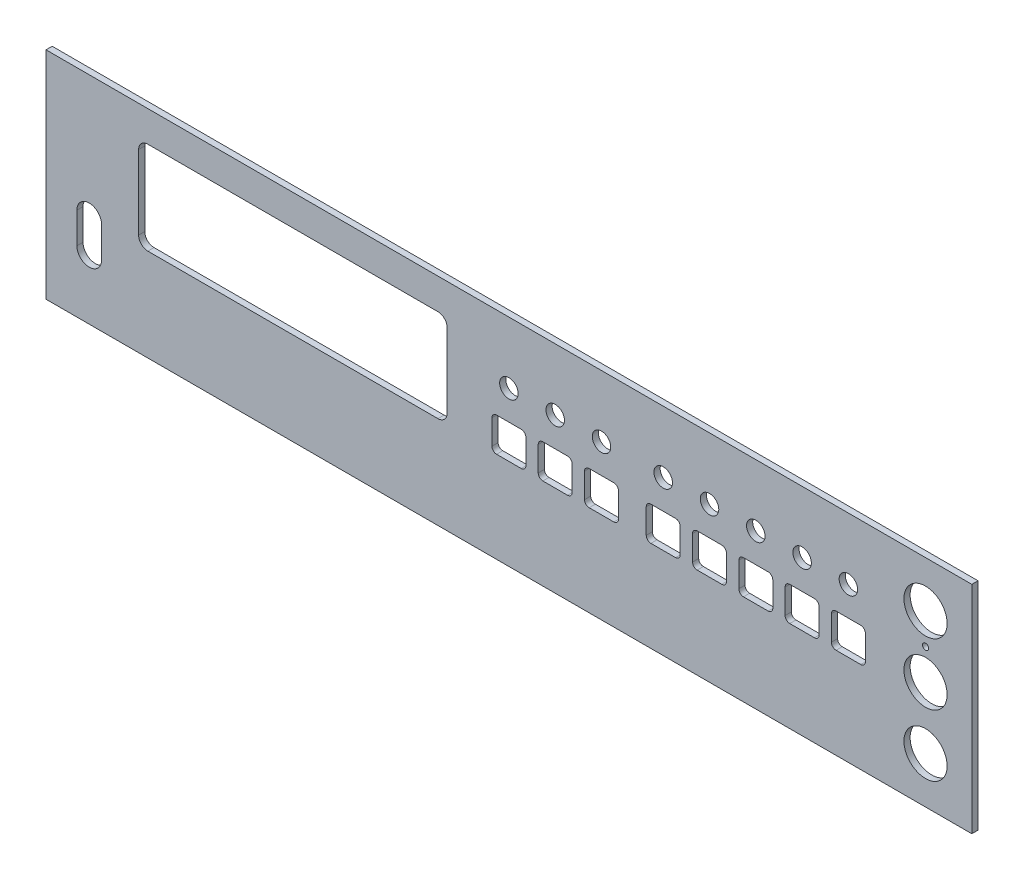
SolidWorks part; units mm, degrees
ref_plane "Спереди" through (0, 0, 0) normal (0, 0, 1) x (1, 0, 0)
ref_plane "Сверху" through (0, 0, 0) normal (0, 1, 0) x (1, 0, 0)
ref_plane "Справа" through (0, 0, 0) normal (1, 0, 0) x (0, 0, -1)
sketch "Эскиз1" plane through (0, 0, 0) normal (0, 0, 1) x (1, 0, 0)
  line L0 (-150, 35) -> (-150, -35) construction
  line L1 (-120, 25) -> (-120, -5) construction
  line L2 (-120, 25) -> (-20, 25) construction
  line L3 (-120, -5) -> (-20, -5) construction
  line L4 (-150, -35) -> (150, -35) construction
  line L5 (-150, 35) -> (150, 35) construction
  line L6 (150, 35) -> (150, -35) construction
  line L7 (70.5, 5.5) -> (70.5, -5.5) construction
  line L8 (59.5, 5.5) -> (70.5, 5.5) construction
  line L9 (59.5, 5.5) -> (59.5, -5.5) construction
  line L10 (59.5, -5.5) -> (70.5, -5.5) construction
  line L11 (74.5, -5.5) -> (85.5, -5.5) construction
  line L12 (74.5, 5.5) -> (74.5, -5.5) construction
  line L13 (74.5, 5.5) -> (85.5, 5.5) construction
  line L14 (85.5, 5.5) -> (85.5, -5.5) construction
  line L15 (89.5, 5.5) -> (89.5, -5.5) construction
  line L16 (89.5, 5.5) -> (100.5, 5.5) construction
  line L17 (100.5, 5.5) -> (100.5, -5.5) construction
  line L18 (104.5, 5.5) -> (104.5, -5.5) construction
  line L19 (89.5, -5.5) -> (100.5, -5.5) construction
  line L20 (104.5, -5.5) -> (115.5, -5.5) construction
  line L21 (115.5, 5.5) -> (115.5, -5.5) construction
  line L22 (104.5, 5.5) -> (115.5, 5.5) construction
  line L23 (44.5, 5.5) -> (55.5, 5.5) construction
  line L24 (44.5, 5.5) -> (44.5, -5.5) construction
  line L25 (44.5, -5.5) -> (55.5, -5.5) construction
  line L26 (55.5, 5.5) -> (55.5, -5.5) construction
  line L27 (9.5, -5.5) -> (9.5, 5.5) construction
  line L28 (9.5, 5.5) -> (20.5, 5.5) construction
  line L29 (20.5, -5.5) -> (20.5, 5.5) construction
  line L30 (9.5, -5.5) -> (20.5, -5.5) construction
  line L31 (24.5, 5.5) -> (35.5, 5.5) construction
  line L32 (35.5, -5.5) -> (35.5, 5.5) construction
  line L33 (24.5, -5.5) -> (35.5, -5.5) construction
  line L34 (24.5, -5.5) -> (24.5, 5.5) construction
  line L35 (-20, 25) -> (-20, -5) construction
  line L36 (-5.5, -5.5) -> (-5.5, 5.5) construction
  line L37 (-5.5, 5.5) -> (5.5, 5.5) construction
  line L38 (5.5, -5.5) -> (5.5, 5.5) construction
  line L39 (-5.5, -5.5) -> (5.5, -5.5) construction
  line L40 (-150, 35) -> (-150, -35)
  line L41 (-120, 25) -> (-120, -5)
  line L42 (-120, 25) -> (-20, 25)
  line L43 (-120, -5) -> (-20, -5)
  line L44 (-150, -35) -> (150, -35)
  line L45 (-150, 35) -> (150, 35)
  line L46 (150, 35) -> (150, -35)
  line L47 (70.5, 5.5) -> (70.5, -5.5)
  line L48 (59.5, 5.5) -> (70.5, 5.5)
  line L49 (59.5, 5.5) -> (59.5, -5.5)
  line L50 (59.5, -5.5) -> (70.5, -5.5)
  line L51 (74.5, -5.5) -> (85.5, -5.5)
  line L52 (74.5, 5.5) -> (74.5, -5.5)
  line L53 (74.5, 5.5) -> (85.5, 5.5)
  line L54 (85.5, 5.5) -> (85.5, -5.5)
  line L55 (89.5, 5.5) -> (89.5, -5.5)
  line L56 (89.5, 5.5) -> (100.5, 5.5)
  line L57 (100.5, 5.5) -> (100.5, -5.5)
  line L58 (104.5, 5.5) -> (104.5, -5.5)
  line L59 (89.5, -5.5) -> (100.5, -5.5)
  line L60 (104.5, -5.5) -> (115.5, -5.5)
  line L61 (115.5, 5.5) -> (115.5, -5.5)
  line L62 (104.5, 5.5) -> (115.5, 5.5)
  line L63 (44.5, 5.5) -> (55.5, 5.5)
  line L64 (44.5, 5.5) -> (44.5, -5.5)
  line L65 (44.5, -5.5) -> (55.5, -5.5)
  line L66 (55.5, 5.5) -> (55.5, -5.5)
  line L67 (9.5, -5.5) -> (9.5, 5.5)
  line L68 (9.5, 5.5) -> (20.5, 5.5)
  line L69 (20.5, -5.5) -> (20.5, 5.5)
  line L70 (9.5, -5.5) -> (20.5, -5.5)
  line L71 (24.5, 5.5) -> (35.5, 5.5)
  line L72 (35.5, -5.5) -> (35.5, 5.5)
  line L73 (24.5, -5.5) -> (35.5, -5.5)
  line L74 (24.5, -5.5) -> (24.5, 5.5)
  line L75 (-20, 25) -> (-20, -5)
  line L76 (-5.5, -5.5) -> (-5.5, 5.5)
  line L77 (-5.5, 5.5) -> (5.5, 5.5)
  line L78 (5.5, -5.5) -> (5.5, 5.5)
  line L79 (-5.5, -5.5) -> (5.5, -5.5)
  line L80 (-140, -5) -> (-140, -15) construction
  line L81 (-132, -5) -> (-132, -15) construction
  line L82 (-140, -5) -> (-140, -15)
  line L83 (-132, -5) -> (-132, -15)
  arc A0 (-132, -5) -> (-140, -5) centre (-136, -5) ccw construction
  circle A1 centre (135, 20) radius 7 construction
  circle A2 centre (135, 0) radius 7 construction
  circle A3 centre (135, -20) radius 7 construction
  circle A4 centre (110, 15) radius 3 construction
  circle A5 centre (95, 15) radius 3 construction
  circle A6 centre (80, 15) radius 3 construction
  circle A7 centre (65, 15) radius 3 construction
  circle A8 centre (50, 15) radius 3 construction
  circle A9 centre (30, 15) radius 3 construction
  circle A10 centre (15, 15) radius 3 construction
  circle A11 centre (0, 15) radius 3 construction
  arc A12 (-132, -5) -> (-140, -5) centre (-136, -5) ccw
  circle A13 centre (135, 20) radius 7
  circle A14 centre (135, 0) radius 7
  circle A15 centre (135, -20) radius 7
  circle A16 centre (110, 15) radius 3
  circle A17 centre (95, 15) radius 3
  circle A18 centre (80, 15) radius 3
  circle A19 centre (65, 15) radius 3
  circle A20 centre (50, 15) radius 3
  circle A21 centre (30, 15) radius 3
  circle A22 centre (15, 15) radius 3
  circle A23 centre (0, 15) radius 3
  arc A24 (-140, -15) -> (-132, -15) centre (-136, -15) ccw construction
  arc A25 (-140, -15) -> (-132, -15) centre (-136, -15) ccw
extrude "Бобышка-Вытянуть1" add sketch "Эскиз1" against normal blind 2
fillet "Скругление1" radius 1.5 32 edges at (55.5, -5.5, -1) (70.5, -5.5, -1) (85.5, -5.5, -1) (100.5, -5.5, -1) (115.5, -5.5, -1) (115.5, 5.5, -1) (44.5, 5.5, -1) (100.5, 5.5, -1) (85.5, 5.5, -1) (70.5, 5.5, -1) (55.5, 5.5, -1) (59.5, 5.5, -1) (74.5, 5.5, -1) (89.5, 5.5, -1) (104.5, 5.5, -1) (104.5, -5.5, -1) (89.5, -5.5, -1) (74.5, -5.5, -1) (59.5, -5.5, -1) (44.5, -5.5, -1) (24.5, -5.5, -1) (35.5, 5.5, -1) (24.5, 5.5, -1) (35.5, -5.5, -1) (20.5, -5.5, -1) (5.5, -5.5, -1) (-5.5, -5.5, -1) (9.5, -5.5, -1) (9.5, 5.5, -1) (20.5, 5.5, -1) (5.5, 5.5, -1) (-5.5, 5.5, -1)
fillet "Скругление2" radius 3 4 edges at (-120, -5, -1) (-120, 25, -1) (-20, -5, -1) (-20, 25, -1)
sketch "Эскиз2" plane through (0, 0, 0) normal (0, 0, 1) x (1, 0, 0)
  circle A0 centre (135, 10) radius 1
  circle A1 centre (135, 20) radius 7 construction
  dimension "D1" = 2
  dimension "D2" = 10
extrude "Вырез-Вытянуть1" cut sketch "Эскиз2" against normal through all
